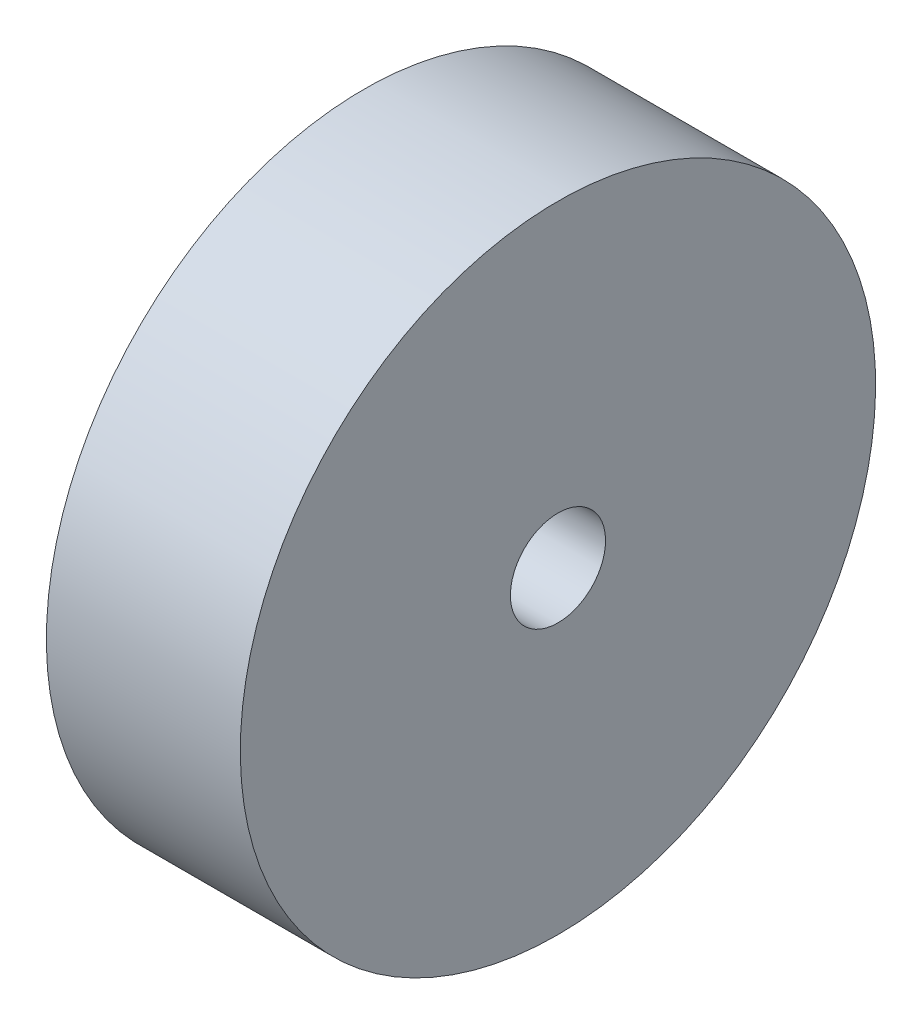
SolidWorks part; units mm, degrees
ref_plane "Front Plane" through (0, 0, 0) normal (0, 0, 1) x (1, 0, 0)
ref_plane "Top Plane" through (0, 0, 0) normal (0, 1, 0) x (1, 0, 0)
ref_plane "Right Plane" through (0, 0, 0) normal (1, 0, 0) x (0, 0, -1)
sketch "Sketch2" plane through (0, 0, 0) normal (0, 0, 1) x (1, 0, 0)
  line L0 (-78.8779, 0) -> (0, 0) construction
  line L3 (-13.25, 6.5) -> (-13.25, 43.4)
  line L4 (-13.25, 43.4) -> (13.25, 43.4)
  line L5 (13.25, 43.4) -> (13.25, 6.5)
  line L12 (0, 0) -> (78.8779, 0) construction
  line L13 (-33.465, 17.5) -> (33.465, 17.5) construction
  line L14 (-13.25, 6.5) -> (13.25, 6.5)
  line L15 (-33.465, 16) -> (33.465, 16) construction
  line L16 (0, -30.374) -> (0, 30.374) construction
  line L17 (-33.465, 12.5) -> (33.465, 12.5) construction
  point P15 (0, 16)
  point P16 (0, 17.5)
  point P20 (0, 6.5)
  dimension "D1" = 13
  dimension "D2" = 86.8
  dimension "D3" = 26.5
  dimension "D4" = 16
  dimension "D5" = 12.5
  dimension "D7" = 17.5
revolve "Revolve1" add sketch "Sketch2" angle 360 about L0
